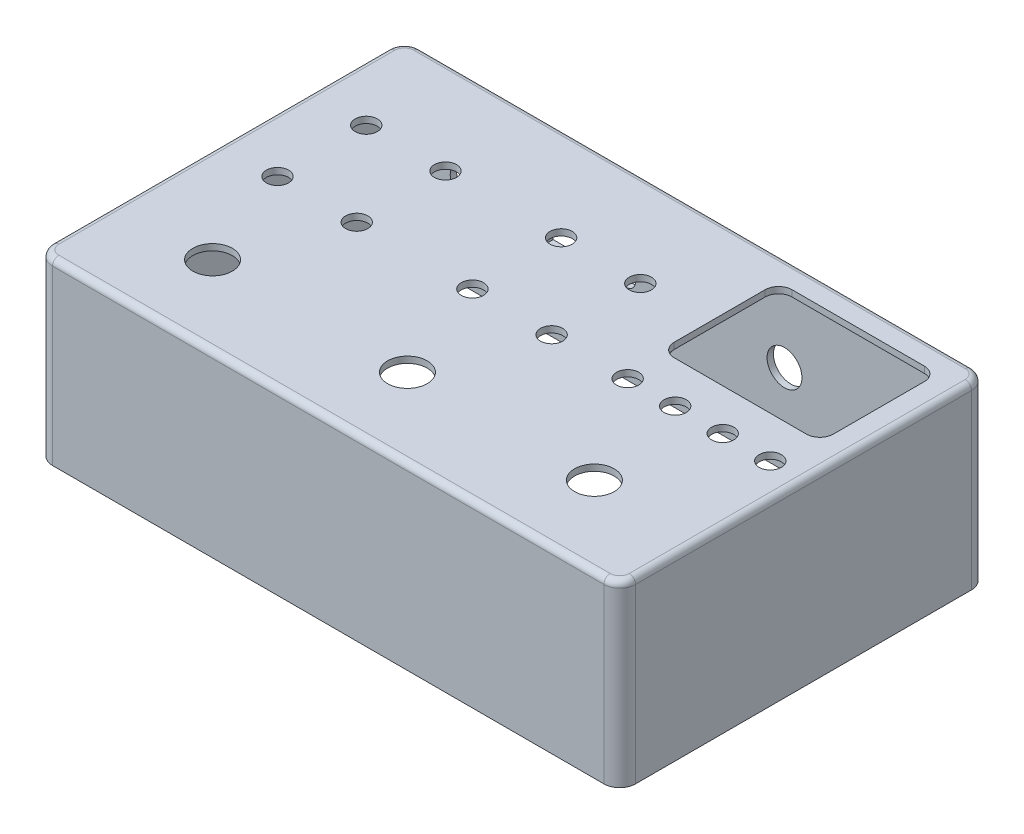
SolidWorks part; units mm, degrees
ref_plane "前视基准面" through (0, 0, 0) normal (0, 0, 1) x (1, 0, 0)
ref_plane "上视基准面" through (0, 0, 0) normal (0, 1, 0) x (1, 0, 0)
ref_plane "右视基准面" through (0, 0, 0) normal (1, 0, 0) x (0, 0, -1)
sketch "草图1" plane through (0, 0, 0) normal (0, 1, 0) x (1, 0, 0)
  line L0 (-126.4002, 28) -> (39.5998, 28) construction
  line L1 (-144.4002, 58) -> (39.5998, 58)
  line L2 (-144.4002, 58) -> (-144.4002, -58)
  line L3 (-144.4002, -58) -> (39.5998, -58)
  line L4 (39.5998, 58) -> (39.5998, -58)
  line L5 (-144.4002, 28) -> (-126.4002, 28) construction
  line L6 (-144.4002, 0) -> (39.5998, 0) construction
  line L7 (-144.4002, -33) -> (39.5998, -33) construction
  line L9 (-14.2652, 50) -> (27.4648, 50)
  line L10 (-18.2652, 46) -> (-18.2652, 17.3)
  line L11 (-14.2652, 13.3) -> (27.4648, 13.3)
  line L12 (31.4648, 46) -> (31.4648, 17.3)
  line L15 (-101.4002, 28) -> (-126.4002, 28) construction
  line L16 (-126.4002, 28) -> (-101.4002, 0) construction
  line L17 (-64.9002, 28) -> (-39.9002, 0) construction
  line L18 (-15.9002, 0) -> (-15.9002, -10) construction
  line L19 (-15.9002, -10) -> (29.0998, -10) construction
  line L20 (29.0998, -10) -> (29.0998, 0) construction
  circle A0 centre (-126.4002, 28) radius 3.5
  circle A1 centre (-101.4002, 28) radius 3.5
  circle A2 centre (-126.4002, 0) radius 3.5
  circle A3 centre (-101.4002, 0) radius 3.5
  circle A4 centre (-64.9002, 28) radius 3.5
  circle A5 centre (-39.9002, 28) radius 3.5
  circle A6 centre (-64.9002, 0) radius 3.5
  circle A7 centre (-39.9002, 0) radius 3.5
  circle A8 centre (-15.9002, 0) radius 3.5
  circle A9 centre (-0.9002, 0) radius 3.5
  circle A10 centre (14.0998, 0) radius 3.5
  circle A11 centre (29.0998, 0) radius 3.5
  circle A12 centre (-113.9002, -33) radius 6.25
  circle A13 centre (-52.4002, -33) radius 6.25
  circle A14 centre (6.5998, -33) radius 6.25
  arc A15 (27.4648, 50) -> (31.4648, 46) centre (27.4648, 46) cw
  arc A16 (-14.2652, 50) -> (-18.2652, 46) centre (-14.2652, 46) ccw
  arc A17 (27.4648, 13.3) -> (31.4648, 17.3) centre (27.4648, 17.3) ccw
  arc A18 (-18.2652, 17.3) -> (-14.2652, 13.3) centre (-14.2652, 17.3) ccw
  point P43 (6.5998, 50)
  point P44 (-113.9002, 14)
  point P49 (31.4648, 50)
  point P52 (-18.2652, 50)
  point P55 (31.4648, 13.3)
  point P59 (-52.4002, 14)
  point P60 (6.5998, -10)
  point P66 (-52.4002, -33)
  dimension "D3" = 30
  dimension "D12" = 7
  dimension "D16" = 12.5
  dimension "D19" = 49.73
  dimension "D23" = 4
  dimension "D1" = 184
  dimension "D2" = 116
  dimension "D4" = 10
  dimension "D5" = 25
  dimension "D6" = 25
  dimension "D9" = 15
  dimension "D10" = 15
  dimension "D11" = 15
  dimension "D13" = 10.5
  dimension "D14" = 61.5
  dimension "D15" = 59
  dimension "D17" = 28
  dimension "D20" = 36.7
  dimension "D21" = 8
  dimension "D22" = 25
extrude "凸台-拉伸1" add sketch "草图1" along normal blind 56.5
sketch "草图3" plane through (0, 0, 0) normal (0, -1, 0) x (1, 0, 0)
  line L1 (36.5998, -55) -> (-141.4002, -55)
  line L2 (36.5998, -55) -> (36.5998, 55)
  line L3 (36.5998, 55) -> (-141.4002, 55)
  line L4 (-144.4002, 58) -> (-144.4002, -58)
  line L5 (-144.4002, -58) -> (39.5998, -58)
  line L6 (39.5998, -58) -> (39.5998, 58)
  line L7 (39.5998, 58) -> (-144.4002, 58)
  line L8 (-144.4002, 58) -> (-144.4002, -58)
  line L9 (-144.4002, -58) -> (39.5998, -58)
  line L10 (39.5998, -58) -> (39.5998, 58)
  line L11 (39.5998, 58) -> (-144.4002, 58)
  line L12 (-141.4002, -55) -> (-141.4002, 55)
  dimension "D2" = 3
  dimension "D3" = 3
  dimension "D4" = 3
  dimension "D5" = 3
  dimension "D1" = 0
extrude "切除-拉伸2" cut sketch "草图3" against normal offset from surface (53.5 mm away) 3 up to face at (-52.4002, 56.5, 39.25)
sketch "草图4" plane through (0, 56.5, 0) normal (0, 1, 0) x (1, 0, 0)
  line L0 (27.4648, 50) -> (-14.2652, 50)
  line L1 (27.4648, 50) -> (-14.2652, 50)
  line L2 (-18.2652, 46) -> (-18.2652, 17.3)
  line L3 (-18.2652, 46) -> (-18.2652, 17.3)
  line L4 (31.4648, 17.3) -> (31.4648, 46)
  line L5 (31.4648, 17.3) -> (31.4648, 46)
  line L6 (-14.2652, 13.3) -> (27.4648, 13.3)
  line L7 (-14.2652, 13.3) -> (27.4648, 13.3)
  arc A0 (-14.2652, 50) -> (-18.2652, 46) centre (-14.2652, 46) ccw
  arc A1 (-14.2652, 50) -> (-18.2652, 46) centre (-14.2652, 46) ccw
  arc A2 (-18.2652, 17.3) -> (-14.2652, 13.3) centre (-14.2652, 17.3) ccw
  arc A3 (-18.2652, 17.3) -> (-14.2652, 13.3) centre (-14.2652, 17.3) ccw
  arc A4 (31.4648, 46) -> (27.4648, 50) centre (27.4648, 46) ccw
  arc A5 (31.4648, 46) -> (27.4648, 50) centre (27.4648, 46) ccw
  arc A6 (27.4648, 13.3) -> (31.4648, 17.3) centre (27.4648, 17.3) ccw
  arc A7 (27.4648, 13.3) -> (31.4648, 17.3) centre (27.4648, 17.3) ccw
extrude "切除-拉伸-薄壁1" cut sketch "草图4" against normal blind 3 thin
fillet "圆角1" radius 5 8 edges at (-144.4002, 28.25, -58) (-144.4002, 28.25, 58) (-141.4002, 26.75, 55) (36.5998, 26.75, -55) (39.5998, 28.25, -58) (39.5998, 28.25, 58) (36.5998, 26.75, 55) (-141.4002, 26.75, -55)
sketch "草图5" plane through (0, 53.5, 0) normal (0, -1, 0) x (1, 0, 0)
  line L0 (31.5998, 55) -> (-136.4002, 55) construction
  line L1 (-138.9002, -52.5) -> (34.0998, -52.5)
  line L2 (-138.9002, -52.5) -> (-138.9002, 52.5)
  line L3 (-138.9002, 52.5) -> (34.0998, 52.5)
  line L4 (34.0998, -52.5) -> (34.0998, 52.5)
  line L5 (-141.4002, -50) -> (-141.4002, 50) construction
  line L6 (36.5998, -50) -> (36.5998, 50) construction
  line L7 (31.5998, -55) -> (-136.4002, -55) construction
  line L8 (34.0998, -49) -> (92.5653, -49) construction
  circle A0 centre (-138.9002, -52.5) radius 3.5
  circle A1 centre (-138.9002, 52.5) radius 3.5
  circle A2 centre (34.0998, 52.5) radius 3.5
  circle A3 centre (34.0998, -52.5) radius 3.5
  arc M34 (-136.4002, 55) -> (-141.4002, 50) centre (-136.4002, 50) ccw
  arc M36 (-141.4002, -50) -> (-136.4002, -55) centre (-136.4002, -50) ccw
  arc M38 (31.5998, -55) -> (36.5998, -50) centre (31.5998, -50) ccw
  arc M40 (36.5998, 50) -> (31.5998, 55) centre (31.5998, 50) ccw
  dimension "D1" = 2.5
  dimension "D5" = 7
  dimension "D2" = 2.5
  dimension "D3" = 2.5
  dimension "D4" = 2.5
extrude "凸台-拉伸2" add sketch "草图5" along normal up to surface (53.5 mm away) contours L3 A1 L2 M34 | L2 A1 L3 | A0 L1 L2 M36 | L1 A0 L2 | L3 A2 L4 | L4 A2 L3 M40 | L4 A3 L1 | A3 L4 L1 M38 up to face at (-52.4002, 0, 0)
sketch "草图6" plane through (0, 0, 0) normal (0, -1, 0) x (1, 0, 0)
  circle A0 centre (34.0998, -52.5) radius 2.25
  circle A1 centre (34.0998, 52.5) radius 2.25
  circle A2 centre (-138.9002, 52.5) radius 2.25
  circle A3 centre (-138.9002, -52.5) radius 2.25
  dimension "D1" = 4.5
extrude "切除-拉伸3" cut sketch "草图6" against normal blind 20
fillet "圆角2" radius 2 8 edges at (-142.9357, 56.5, 56.5355) (-142.9357, 56.5, -56.5355) (38.1354, 56.5, -56.5355) (38.1354, 56.5, 56.5355) (39.5998, 56.5, 0) (-52.4002, 56.5, -58) (-144.4002, 56.5, 0) (-52.4002, 56.5, 58)
sketch "草图7" plane through (0, 0, -58) normal (0, 0, -1) x (-1, 0, 0)
  line L0 (-34.5998, 28.25) -> (139.4002, 28.25) construction
  line L3 (-34.5998, 54.5) -> (-34.5998, 0) construction
  line L4 (139.4002, 0) -> (139.4002, 54.5) construction
  line L5 (-34.5998, 56.5) -> (139.4002, 56.5) construction
  line L8 (87.4002, 31.75) -> (97.4002, 31.75)
  line L9 (87.4002, 31.75) -> (87.4002, 24.75)
  line L10 (87.4002, 24.75) -> (97.4002, 24.75)
  line L11 (97.4002, 31.75) -> (97.4002, 24.75)
  line L12 (83.9002, 30) -> (100.9002, 30)
  line L13 (83.9002, 30) -> (83.9002, 26.5)
  line L14 (83.9002, 26.5) -> (100.9002, 26.5)
  line L15 (100.9002, 30) -> (100.9002, 26.5)
  circle A0 centre (52.4002, 28.25) radius 5.5
  circle A1 centre (122.4002, 28.25) radius 5.5
  circle A3 centre (83.9002, 28.25) radius 1.75
  circle A4 centre (100.9002, 28.25) radius 1.75
  circle A5 centre (22.4002, 28.25) radius 5.5
  circle A6 centre (-17.5998, 28.25) radius 5.5
  circle A7 centre (72.4002, 28.25) radius 3
  point P14 (87.4002, 28.25)
  point P21 (92.4002, 31.75)
  point P22 (52.4002, 28.25)
  point P29 (92.4002, 30)
  dimension "D2" = 30
  dimension "D5" = 11
  dimension "D6" = 11
  dimension "D7" = 3.5
  dimension "D3" = 3.5
  dimension "D11" = 11
  dimension "D14" = 6
  dimension "D1" = 28.25
  dimension "D4" = 17
  dimension "D8" = 3.5
  dimension "D9" = 7
  dimension "D10" = 40
  dimension "D12" = 30
  dimension "D13" = 40
  dimension "D15" = 20
  dimension "D16" = 10
extrude "切除-拉伸4" cut sketch "草图7" against normal blind 20 contours A1 L0 | A6 L0 | L0 A6 | A5 L0 | L0 A5 | A7 L0 | L8 L11 L10 L9 | A3 | A4
sketch "草图8" plane through (-144.4002, 0, 0) normal (-1, 0, 0) x (0, 0, 1)
  line L0 (-58, 0) -> (-58, 54.5) construction
  line L1 (-53, 56.5) -> (53, 56.5) construction
  circle A0 centre (-33, 37.75) radius 5
  dimension "D1" = 25
  dimension "D3" = 10
  dimension "D2" = 18.75
sketch "草图10" plane through (0, 53.5, 0) normal (0, -1, 0) x (1, 0, 0)
  line L4 (36.5998, -50) -> (36.5998, 50)
  line L5 (31.5998, 55) -> (-136.4002, 55)
  line L6 (-141.4002, 50) -> (-141.4002, -50)
  line L7 (-136.4002, -55) -> (31.5998, -55)
  line L8 (36.5998, -50) -> (36.5998, 50)
  line L9 (31.5998, 55) -> (-136.4002, 55)
  line L10 (-141.4002, 50) -> (-141.4002, -50)
  line L11 (-136.4002, -55) -> (31.5998, -55)
  arc A12 (36.5996, -50.0503) -> (31.6501, -54.9997) centre (34.0998, -52.5) ccw
  arc A13 (36.5996, -50.0503) -> (36.5998, -50) centre (31.5998, -50) ccw
  arc A14 (36.5998, 50) -> (36.5996, 50.0503) centre (31.5998, 50) ccw
  arc A15 (31.6501, 54.9997) -> (36.5996, 50.0503) centre (34.0998, 52.5) ccw
  arc A16 (31.6501, 54.9997) -> (31.5998, 55) centre (31.5998, 50) ccw
  arc A17 (-136.4002, 55) -> (-136.4504, 54.9997) centre (-136.4002, 50) ccw
  arc A18 (-141.3999, 50.0503) -> (-136.4504, 54.9997) centre (-138.9002, 52.5) ccw
  arc A19 (-141.3999, 50.0503) -> (-141.4002, 50) centre (-136.4002, 50) ccw
  arc A20 (-141.4002, -50) -> (-141.3999, -50.0503) centre (-136.4002, -50) ccw
  arc A21 (-136.4504, -54.9997) -> (-141.3999, -50.0503) centre (-138.9002, -52.5) ccw
  arc A22 (-136.4504, -54.9997) -> (-136.4002, -55) centre (-136.4002, -50) ccw
  arc A23 (31.5998, -55) -> (31.6501, -54.9997) centre (31.5998, -50) ccw
  arc A24 (36.5996, -50.0503) -> (31.6501, -54.9997) centre (34.0998, -52.5) ccw
  arc A25 (36.5996, -50.0503) -> (36.5998, -50) centre (31.5998, -50) ccw
  arc A26 (36.5998, 50) -> (36.5996, 50.0503) centre (31.5998, 50) ccw
  arc A27 (31.6501, 54.9997) -> (36.5996, 50.0503) centre (34.0998, 52.5) ccw
  arc A28 (31.6501, 54.9997) -> (31.5998, 55) centre (31.5998, 50) ccw
  arc A29 (-136.4002, 55) -> (-136.4504, 54.9997) centre (-136.4002, 50) ccw
  arc A30 (-141.3999, 50.0503) -> (-136.4504, 54.9997) centre (-138.9002, 52.5) ccw
  arc A31 (-141.3999, 50.0503) -> (-141.4002, 50) centre (-136.4002, 50) ccw
  arc A32 (-141.4002, -50) -> (-141.3999, -50.0503) centre (-136.4002, -50) ccw
  arc A33 (-136.4504, -54.9997) -> (-141.3999, -50.0503) centre (-138.9002, -52.5) ccw
  arc A34 (-136.4504, -54.9997) -> (-136.4002, -55) centre (-136.4002, -50) ccw
  arc A35 (31.5998, -55) -> (31.6501, -54.9997) centre (31.5998, -50) ccw
  dimension "D1" = 0
extrude "切除-拉伸5" cut sketch "草图10" against normal blind 1
sketch "草图11" plane through (0, 0, -55) normal (0, 0, 1) x (1, 0, 0)
  line L4 (-136.4002, 0) -> (31.5998, 0)
  line L5 (31.5998, 0) -> (31.5998, 54.5)
  line L6 (31.5998, 54.5) -> (-136.4002, 54.5)
  line L7 (-136.4002, 54.5) -> (-136.4002, 0)
  line L8 (-136.4002, 0) -> (31.5998, 0)
  line L9 (31.5998, 0) -> (31.5998, 54.5)
  line L10 (31.5998, 54.5) -> (-136.4002, 54.5)
  line L11 (-136.4002, 54.5) -> (-136.4002, 0)
  dimension "D1" = 0
extrude "切除-拉伸6" cut sketch "草图11" against normal blind 1 contours L8 L9 L10 L11
sketch "草图9" plane through (0, 0, 0) normal (0, -1, 0) x (1, 0, 0)
  line L0 (-141.4002, -50) -> (-141.4002, 50) construction
  line L1 (31.5998, 55) -> (-136.4002, 55) construction
  line L2 (31.5998, -55) -> (-136.4002, -55) construction
  line L3 (36.5998, -50) -> (36.5998, 50) construction
  line L4 (-144.4002, 53) -> (-144.4002, -53)
  line L5 (-139.4002, -58) -> (34.5998, -58)
  line L6 (39.5998, -53) -> (39.5998, 53)
  line L7 (34.5998, 58) -> (-139.4002, 58)
  line L8 (-144.4002, 53) -> (-144.4002, -53)
  line L9 (-139.4002, -58) -> (34.5998, -58)
  line L10 (39.5998, -53) -> (39.5998, 53)
  line L11 (34.5998, 58) -> (-139.4002, 58)
  line L12 (-141.4002, -50) -> (-141.4002, 50)
  line L13 (31.5998, 55) -> (-136.4002, 55)
  line L14 (31.5998, -55) -> (-136.4002, -55)
  line L15 (36.5998, -50) -> (36.5998, 50)
  arc A0 (-136.4504, -54.9997) -> (-141.3999, -50.0503) centre (-138.9002, -52.5) ccw construction
  arc A1 (-141.3999, 50.0503) -> (-136.4504, 54.9997) centre (-138.9002, 52.5) ccw construction
  arc A2 (31.6501, 54.9997) -> (36.5996, 50.0503) centre (34.0998, 52.5) ccw construction
  arc A3 (36.5996, -50.0503) -> (31.6501, -54.9997) centre (34.0998, -52.5) ccw construction
  arc A12 (-136.4504, -54.9997) -> (-141.3999, -50.0503) centre (-138.9002, -52.5) ccw
  arc A13 (-141.3999, 50.0503) -> (-136.4504, 54.9997) centre (-138.9002, 52.5) ccw
  arc A14 (31.6501, 54.9997) -> (36.5996, 50.0503) centre (34.0998, 52.5) ccw
  arc A15 (36.5996, -50.0503) -> (31.6501, -54.9997) centre (34.0998, -52.5) ccw
  arc A16 (31.6501, 54.9997) -> (31.5998, 55) centre (31.5998, 50) ccw construction
  arc A17 (31.6501, 54.9997) -> (31.5998, 55) centre (31.5998, 50) ccw
  arc A18 (36.5998, 50) -> (36.5996, 50.0503) centre (31.5998, 50) ccw construction
  arc A19 (36.5998, 50) -> (36.5996, 50.0503) centre (31.5998, 50) ccw
  arc A20 (36.5996, -50.0503) -> (36.5998, -50) centre (31.5998, -50) ccw construction
  arc A21 (36.5996, -50.0503) -> (36.5998, -50) centre (31.5998, -50) ccw
  arc A22 (31.5998, -55) -> (31.6501, -54.9997) centre (31.5998, -50) ccw construction
  arc A23 (31.5998, -55) -> (31.6501, -54.9997) centre (31.5998, -50) ccw
  arc A24 (-141.4002, -50) -> (-141.3999, -50.0503) centre (-136.4002, -50) ccw construction
  arc A25 (-141.4002, -50) -> (-141.3999, -50.0503) centre (-136.4002, -50) ccw
  arc A26 (-136.4504, -54.9997) -> (-136.4002, -55) centre (-136.4002, -50) ccw construction
  arc A27 (-136.4504, -54.9997) -> (-136.4002, -55) centre (-136.4002, -50) ccw
  arc A28 (-141.3999, 50.0503) -> (-141.4002, 50) centre (-136.4002, 50) ccw construction
  arc A29 (-141.3999, 50.0503) -> (-141.4002, 50) centre (-136.4002, 50) ccw
  arc A30 (-136.4002, 55) -> (-136.4504, 54.9997) centre (-136.4002, 50) ccw construction
  arc A31 (-136.4002, 55) -> (-136.4504, 54.9997) centre (-136.4002, 50) ccw
  arc A32 (-144.4002, -53) -> (-139.4002, -58) centre (-139.4002, -53) ccw
  arc A33 (-144.4002, -53) -> (-139.4002, -58) centre (-139.4002, -53) ccw
  arc A34 (34.5998, -58) -> (39.5998, -53) centre (34.5998, -53) ccw
  arc A35 (34.5998, -58) -> (39.5998, -53) centre (34.5998, -53) ccw
  arc A36 (39.5998, 53) -> (34.5998, 58) centre (34.5998, 53) ccw
  arc A37 (39.5998, 53) -> (34.5998, 58) centre (34.5998, 53) ccw
  arc A38 (-139.4002, 58) -> (-144.4002, 53) centre (-139.4002, 53) ccw
  arc A39 (-139.4002, 58) -> (-144.4002, 53) centre (-139.4002, 53) ccw
  dimension "D1" = 0
